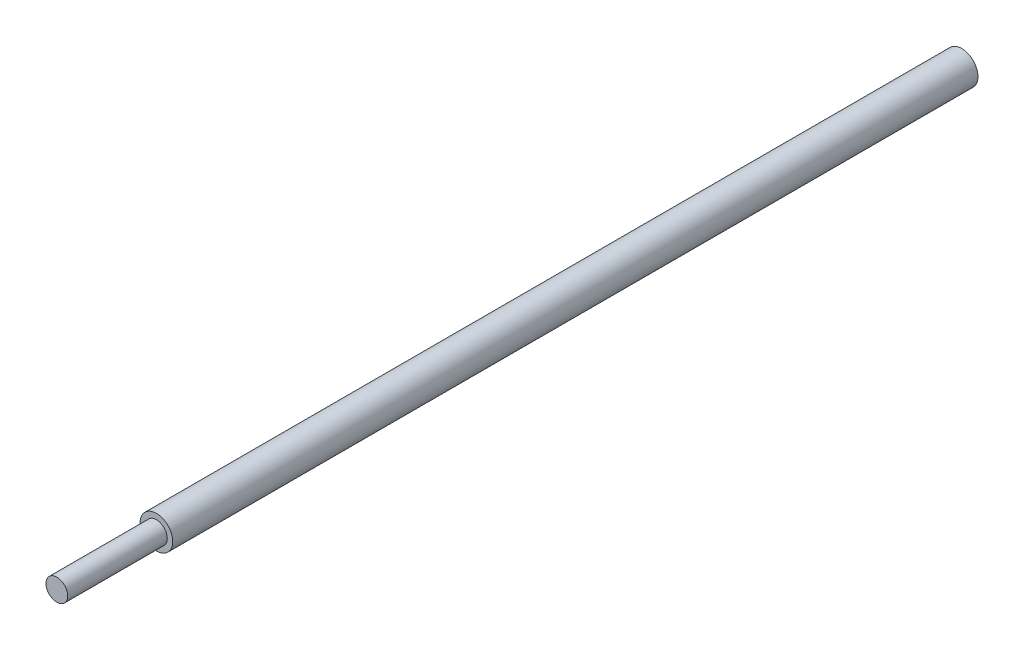
SolidWorks part; units mm, degrees
ref_plane "Front Plane" through (0, 0, 0) normal (0, 0, 1) x (1, 0, 0)
ref_plane "Top Plane" through (0, 0, 0) normal (0, 1, 0) x (1, 0, 0)
ref_plane "Right Plane" through (0, 0, 0) normal (1, 0, 0) x (0, 0, -1)
sketch "Sketch2" plane through (0, 0, 0) normal (0, 0, 1) x (1, 0, 0)
  circle A0 centre (0, 0) radius 3
  dimension "D1" = 6
extrude "Boss-Extrude1" add sketch "Sketch2" along normal mid plane 166.5
sketch "Sketch3" plane through (0, 0, 83.25) normal (0, 0, 1) x (1, 0, 0)
  circle A0 centre (0, 0) radius 2
  circle A1 centre (0, 0) radius 3
  circle A2 centre (0, 0) radius 3 construction
  dimension "D1" = 1
extrude "Cut-Extrude1" cut sketch "Sketch3" against normal blind 18.32
